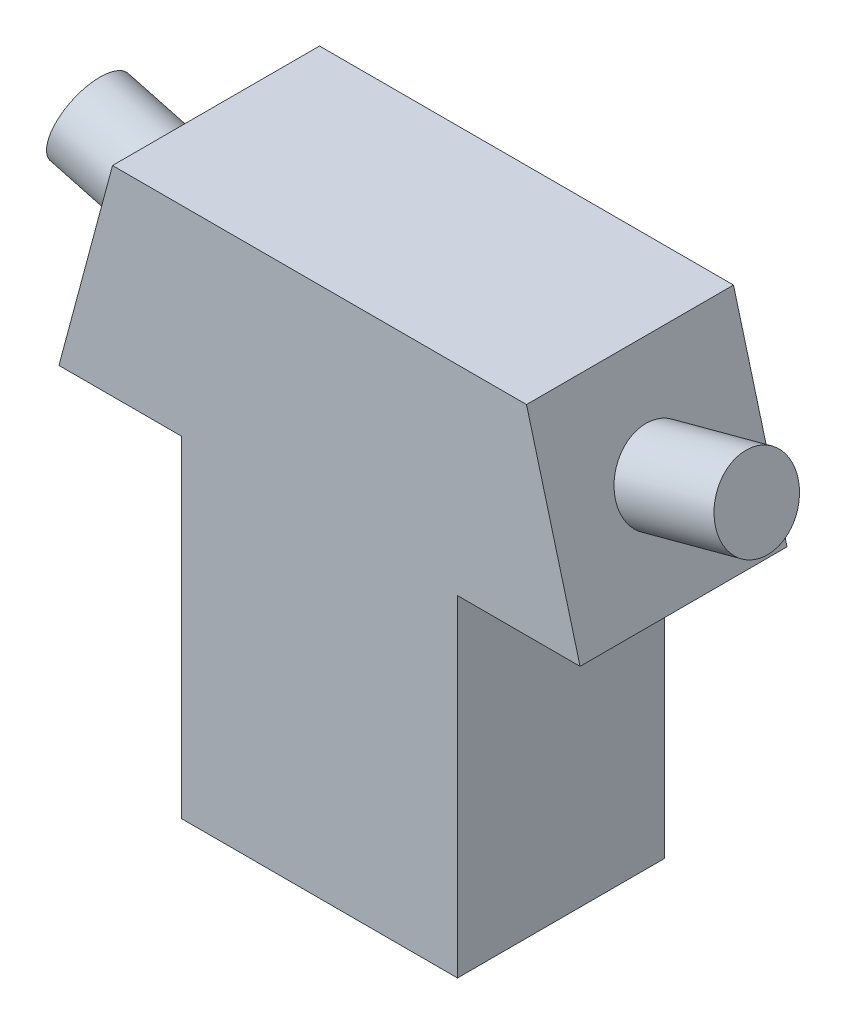
SolidWorks part; units mm, degrees
ref_plane "前视基准面" through (0, 0, 0) normal (0, 0, 1) x (1, 0, 0)
ref_plane "上视基准面" through (0, 0, 0) normal (0, 1, 0) x (1, 0, 0)
ref_plane "右视基准面" through (0, 0, 0) normal (1, 0, 0) x (0, 0, -1)
other "Configuration Table"
sketch "草图1" plane through (0, 0, 0) normal (0, 0, 1) x (1, 0, 0)
  line L0 (0, 0) -> (0, 307.5288) construction
  line L1 (-100, 0) -> (100, 0)
  line L2 (100, 0) -> (100, 240)
  line L3 (100, 240) -> (188.8229, 240)
  line L4 (188.8229, 240) -> (150, 384.8889)
  line L5 (150, 384.8889) -> (-150, 384.8889)
  line L6 (-188.8229, 240) -> (-150, 384.8889)
  line L7 (-100, 240) -> (-188.8229, 240)
  line L8 (-100, 0) -> (-100, 240)
  point P9 (0, 384.8889)
  point P12 (192.8677, 445.6829)
  point P13 (274.1482, 300)
  dimension "D1" = 200
  dimension "D2" = 240
  dimension "D3" = 150
  dimension "D4" = 75
  dimension "D5" = 150
extrude "凸台-拉伸1" add sketch "草图1" along normal blind 150
sketch "草图3" plane through (236.1741, 63.2827, 0) normal (0.9659, 0.2588, 0) x (0, 0, -1)
  line L0 (-75, 541.409) -> (-75, -85.8628) construction
  line L1 (0, -25.8819) -> (0, 205.9403) construction
  line L2 (-150, -25.8819) -> (-150, 205.9403) construction
  line L3 (-75, 257.9512) -> (121.2922, 257.9512) construction
  line L4 (-150, 332.9512) -> (0, 332.9512) construction
  line L5 (-150, 182.9512) -> (0, 182.9512) construction
  circle A0 centre (-75, 257.9512) radius 30
  dimension "D1" = 60
extrude "凸台-拉伸2" add sketch "草图3" along normal blind 75
ref_plane "基准面1" through (0, 0, 0) normal (-1, 0, 0) x (0, 0, 1)
mirror "镜向1" about plane through (0, 0, 0) normal (-1, 0, 0) of "凸台-拉伸2"
sketch "草图4" plane through (0, 0, 0) normal (0, -1, 0) x (1, 0, 0)
  line L0 (-382.5363, 75) -> (303.1719, 75) construction
  line L1 (0, 311.3076) -> (0, -125.5932) construction
  line L2 (-100, 0) -> (100, 0) construction
  line L3 (-100, 150) -> (100, 150) construction
  line L4 (100, 150) -> (100, 0) construction
  line L5 (-100, 150) -> (-100, 0) construction
  circle A0 centre (0, 75) radius 50
  point P14 (0, 100)
  point P15 (59.1265, 100)
  point P16 (0, 0)
  dimension "D1" = 100
extrude "切除-拉伸1" cut sketch "草图4" against normal blind 100
